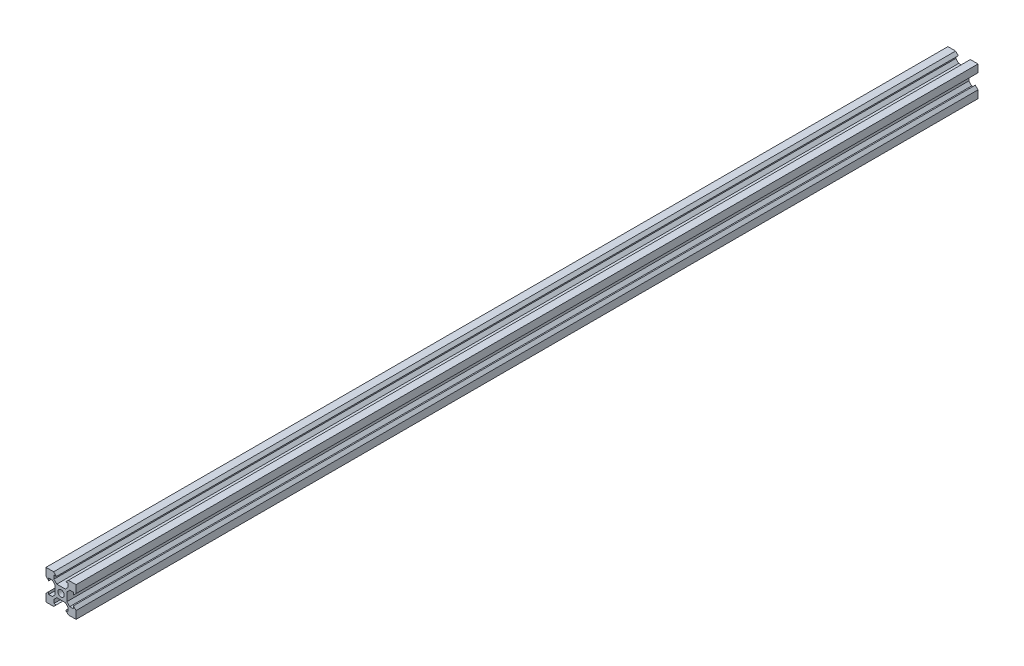
SolidWorks part; units mm, degrees
material "6063-T5"
ref_plane "Front Plane" through (0, 0, 0) normal (0, 0, 1) x (1, 0, 0)
ref_plane "Top Plane" through (0, 0, 0) normal (0, 1, 0) x (1, 0, 0)
ref_plane "Right Plane" through (0, 0, 0) normal (1, 0, 0) x (0, 0, -1)
sketch "Sketch1" plane through (0, 0, 0) normal (0, 0, 1) x (1, 0, 0)
  line L0 (-3.9007, -2.84) -> (-3.9007, 2.84)
  line L1 (-3.9007, 2.84) -> (-5.8007, 4.74)
  line L2 (-5.8007, 4.74) -> (-8.2, 4.74)
  line L3 (-8.2, 4.74) -> (-8.2, 3.1)
  line L4 (-10, 10) -> (-1.4849, 1.4849) construction
  line L5 (0, 3.9007) -> (-2.84, 3.9007)
  line L6 (-2.84, 3.9007) -> (-4.74, 5.8007)
  line L7 (-4.74, 8.2) -> (-3.1, 8.2)
  line L8 (-4.74, 5.8007) -> (-4.74, 8.2)
  line L9 (-3.1, 8.2) -> (-4.9, 10)
  line L10 (-4.9, 10) -> (-10, 10)
  line L11 (-10, 10) -> (-10, 4.9)
  line L12 (-8.2, 3.1) -> (-10, 4.9)
  line L13 (0, 3.9007) -> (0, -3.9007) construction
  line L14 (10, 10) -> (1.4849, 1.4849) construction
  line L15 (8.2, 3.1) -> (10, 4.9)
  line L16 (10, 10) -> (10, 4.9)
  line L17 (4.9, 10) -> (10, 10)
  line L18 (3.1, 8.2) -> (4.9, 10)
  line L19 (4.74, 5.8007) -> (4.74, 8.2)
  line L20 (4.74, 8.2) -> (3.1, 8.2)
  line L21 (2.84, 3.9007) -> (4.74, 5.8007)
  line L22 (8.2, 4.74) -> (8.2, 3.1)
  line L23 (5.8007, 4.74) -> (8.2, 4.74)
  line L24 (3.9007, 2.84) -> (5.8007, 4.74)
  line L25 (2.84, 3.9007) -> (0, 3.9007)
  line L26 (3.9007, 2.84) -> (3.9007, -2.84)
  line L27 (-3.9007, 0) -> (3.9007, 0) construction
  line L28 (10, -10) -> (1.4849, -1.4849) construction
  line L29 (-10, -10) -> (-1.4849, -1.4849) construction
  line L30 (2.84, -3.9007) -> (0, -3.9007)
  line L31 (3.9007, -2.84) -> (5.8007, -4.74)
  line L32 (5.8007, -4.74) -> (8.2, -4.74)
  line L33 (8.2, -4.74) -> (8.2, -3.1)
  line L34 (2.84, -3.9007) -> (4.74, -5.8007)
  line L35 (4.74, -8.2) -> (3.1, -8.2)
  line L36 (4.74, -5.8007) -> (4.74, -8.2)
  line L37 (3.1, -8.2) -> (4.9, -10)
  line L38 (4.9, -10) -> (10, -10)
  line L39 (10, -10) -> (10, -4.9)
  line L40 (8.2, -3.1) -> (10, -4.9)
  line L41 (-8.2, -3.1) -> (-10, -4.9)
  line L42 (-10, -10) -> (-10, -4.9)
  line L43 (-4.9, -10) -> (-10, -10)
  line L44 (-3.1, -8.2) -> (-4.9, -10)
  line L45 (-4.74, -5.8007) -> (-4.74, -8.2)
  line L46 (-4.74, -8.2) -> (-3.1, -8.2)
  line L47 (-2.84, -3.9007) -> (-4.74, -5.8007)
  line L48 (0, -3.9007) -> (-2.84, -3.9007)
  line L49 (-8.2, -4.74) -> (-8.2, -3.1)
  line L50 (-5.8007, -4.74) -> (-8.2, -4.74)
  line L51 (-3.9007, -2.84) -> (-5.8007, -4.74)
  circle A0 centre (0, 0) radius 2.1
  point P10 (-4.8507, 3.79)
  dimension "D1" = 4.2
  dimension "D2" = 5.68
  dimension "D3" = 1.64
  dimension "D4" = 6.2
  dimension "D5" = 0.75
  dimension "D6" = 10
  dimension "D7" = 90
  dimension "D8" = 1.8
extrude "Boss-Extrude1" add sketch "Sketch1" along normal mid plane 600
